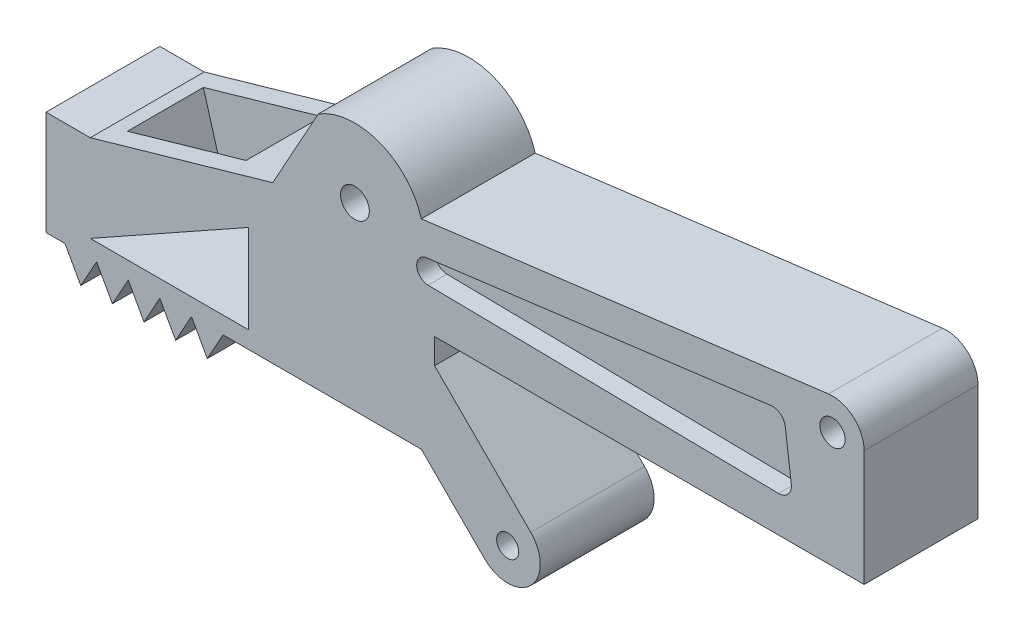
SolidWorks part; units mm, degrees
ref_plane "Front Plane" through (0, 0, 0) normal (0, 0, 1) x (1, 0, 0)
ref_plane "Top Plane" through (0, 0, 0) normal (0, 1, 0) x (1, 0, 0)
ref_plane "Right Plane" through (0, 0, 0) normal (1, 0, 0) x (0, 0, -1)
sketch "Sketch1" plane through (0, 0, 0) normal (0, 0, 1) x (1, 0, 0)
  line L0 (0, 0) -> (15.6704, 0)
  line L1 (-12.5, 0) -> (-14, 0)
  line L2 (-5, 0) -> (-3.75, -2.25)
  line L3 (0, 0) -> (-1.25, -2.25)
  line L4 (-2.5, 0) -> (-3.75, -2.25)
  line L5 (-2.5, 0) -> (-1.25, -2.25)
  line L6 (-7.5, 0) -> (-6.25, -2.25)
  line L7 (-5, 0) -> (-6.25, -2.25)
  line L8 (-10, 0) -> (-8.75, -2.25)
  line L9 (-7.5, 0) -> (-8.75, -2.25)
  line L10 (-12.5, 0) -> (-11.25, -2.25)
  line L11 (-10, 0) -> (-11.25, -2.25)
  line L12 (-14, 0) -> (-14, 8.2432)
  line L13 (-14, 8.2432) -> (-10.5, 8.2432)
  line L14 (-10.5, 8.2432) -> (3.9189, 12.3777)
  line L15 (3.9189, 12.3777) -> (10.4189, 14.2416) construction
  line L16 (3.9189, 12.3777) -> (7.5219, 18.8777)
  line L17 (15.6669, 15.7729) -> (47.8502, 19.8834)
  line L18 (12.3662, 19.3499) -> (15.5732, 18.1274) construction
  line L19 (15.6669, 15.7729) -> (15.5732, 18.1274) construction
  line L20 (50.6669, 17.4036) -> (50.6669, 8.2432)
  line L21 (50.6669, 8.2432) -> (16.7125, 8.2432)
  line L22 (16.7125, 8.2432) -> (16.7125, 6.2432)
  line L23 (15.6704, 0) -> (20.6704, -5)
  line L25 (24.3131, -1.3574) -> (16.7125, 6.2432)
  arc A0 (15.6669, 15.7729) -> (7.5219, 18.8777) centre (10.4189, 14.2416) ccw
  circle A1 centre (10.4189, 14.2416) radius 1.1375
  arc A2 (20.6704, -5) -> (24.3131, -1.3574) centre (22.4917, -3.1787) ccw
  circle A3 centre (22.4917, -3.1787) radius 0.875
  arc A4 (50.6669, 17.4036) -> (47.8502, 19.8834) centre (48.1669, 17.4036) ccw
  circle A5 centre (48.1669, 17.4036) radius 1
  point P33 (50.6669, 20.2432)
  dimension "D8" = 2.275
  dimension "D15" = 1.75
  dimension "D16" = 2.5
  dimension "D17" = 2
  dimension "D1" = 3.5
  dimension "D2" = 5
  dimension "D3" = 15
  dimension "D4" = 164
  dimension "D5" = 6.5
  dimension "D6" = 45
  dimension "D7" = 6.5
  dimension "D9" = 85
  dimension "D10" = 35
  dimension "D11" = 12
  dimension "D12" = 5
  dimension "D13" = 135
  dimension "D14" = 2
extrude "Boss-Extrude1" add sketch "Sketch1" along normal blind 9
ref_plane "Plane1" through (0, 0, 4.5) normal (0, 0, 1) x (1, 0, 0)
sketch "Sketch3" plane through (0, 0, 9) normal (0, 0, 1) x (1, 0, 0)
  line L0 (-14, 0) -> (-10, 0)
  line L1 (-10.5, 1.35) -> (2, 1.35)
  line L2 (2, 1.35) -> (2, 8.35)
  line L3 (2, 8.35) -> (-10.5, 1.35)
  dimension "D1" = 1.35
  dimension "D2" = 12.5
extrude "Cut-Extrude1" cut sketch "Sketch3" against normal through all contours L3 L1 L2
sketch "Sketch4" plane through (-2.9819, 10.399, 0) normal (-0.2756, 0.9613, 0) x (0.9613, 0.2756, 0)
  line L3 (-6.3211, -7.5) -> (3.4289, -7.5)
  line L4 (3.4289, -7.5) -> (3.4289, -1.5)
  line L5 (3.4289, -1.5) -> (-6.3211, -1.5)
  line L6 (-6.3211, -1.5) -> (-6.3211, -7.5)
extrude "Cut-Extrude2" cut sketch "Sketch4" against normal up to next
sketch "Sketch5" plane through (0, 0, 9) normal (0, 0, 1) x (1, 0, 0)
  line L0 (15.6669, 15.7729) -> (16.2003, 13.3304) construction
  line L2 (16.2003, 13.3304) -> (44.3039, 16.9397)
  line L3 (44.3039, 16.9397) -> (45.0567, 11.0774)
  line L4 (45.0567, 11.0774) -> (16.2003, 11.4986)
  arc A0 (16.2003, 11.4986) -> (16.2003, 13.3304) centre (16.2137, 12.4145) cw
  dimension "D1" = 95
extrude "Cut-Extrude3" cut sketch "Sketch5" against normal blind 1.5
fillet "Fillet1" radius 1 2 edges at (45.0567, 11.0774, 8.25) (44.3039, 16.9397, 8.25)
mirror "Mirror1" about plane through (0, 0, 4.5) normal (0, 0, 1) of "Fillet1", "Cut-Extrude3"
